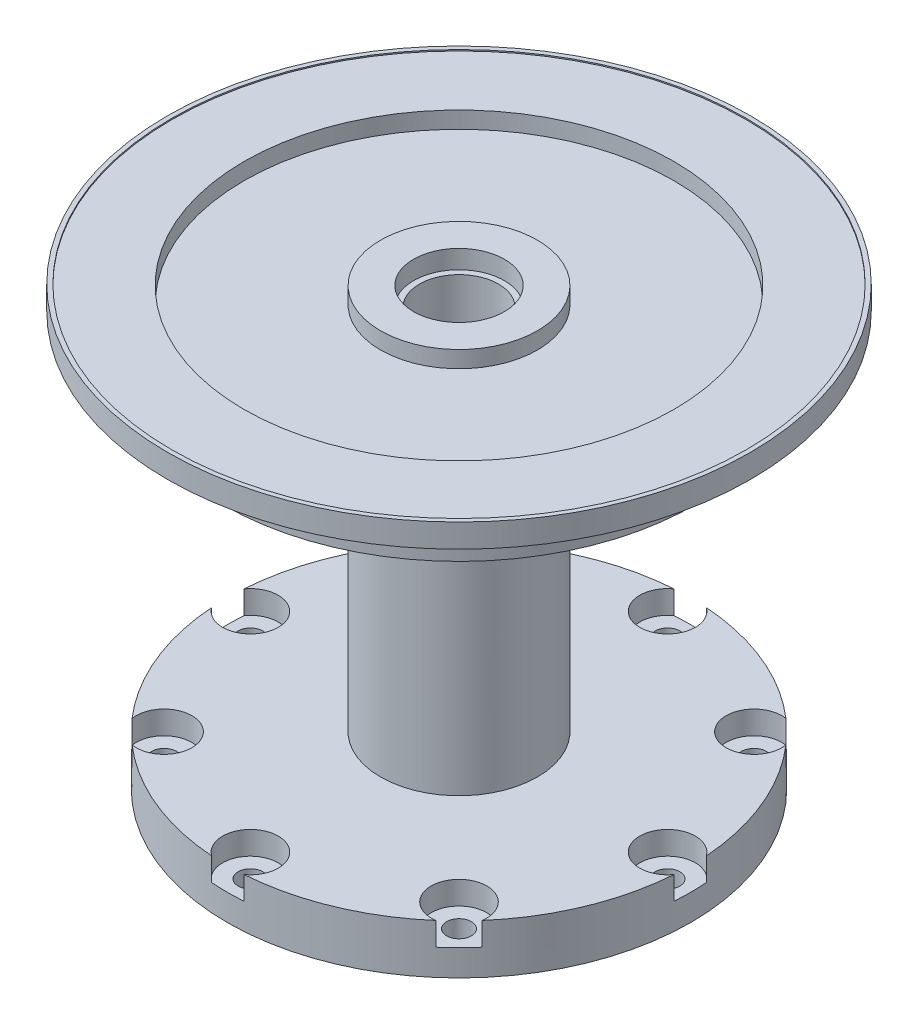
SolidWorks part; units mm, degrees
material "AISI 304"
ref_plane "Front Plane" through (0, 0, 0) normal (0, 0, 1) x (1, 0, 0)
ref_plane "Top Plane" through (0, 0, 0) normal (0, 1, 0) x (1, 0, 0)
ref_plane "Right Plane" through (0, 0, 0) normal (1, 0, 0) x (0, 0, -1)
sketch "Sketch1" plane through (0, 0, 0) normal (0, 1, 0) x (1, 0, 0)
  circle A0 centre (0, 0) radius 38.1
  dimension "D1" = 76.2
extrude "Boss-Extrude1" add sketch "Sketch1" along normal blind 4.826
sketch "Sketch2" plane through (0, 4.826, 0) normal (0, 1, 0) x (1, 0, 0)
  circle A0 centre (0, 0) radius 38.1 construction
  circle A1 centre (0, 0) radius 38.1
extrude "Boss-Extrude2" add sketch "Sketch2" along normal blind 3.302 draft 70 draft outward yes
sketch "Sketch3" plane through (0, 8.128, 0) normal (0, 1, 0) x (1, 0, 0)
  circle A0 centre (0, 0) radius 47.1722 construction
  circle A1 centre (0, 0) radius 47.1722
extrude "Boss-Extrude3" add sketch "Sketch3" along normal blind 3.81
sketch "Sketch4" plane through (0, 11.938, 0) normal (0, 1, 0) x (1, 0, 0)
  circle A3 centre (0, 0) radius 46.4722
  circle A4 centre (0, 0) radius 46.4722
  dimension "D1" = 0.7
extrude "Cut-Extrude1" cut sketch "Sketch4" against normal blind 0.2
sketch "Sketch6" plane through (0, 11.738, 0) normal (0, 1, 0) x (1, 0, 0)
  circle A1 centre (0, 0) radius 12.7
  circle A2 centre (0, 0) radius 34.7722
  circle A3 centre (0, 0) radius 34.7722
  dimension "D2" = 25.4
  dimension "D1" = 11.7
extrude "Cut-Extrude2" cut sketch "Sketch6" against normal blind 2.7
sketch "Sketch7" plane through (0, 11.738, 0) normal (0, 1, 0) x (1, 0, 0)
  circle A0 centre (0, 0) radius 5.35
  dimension "D1" = 10.7
sketch "Sketch8" plane through (0, 0, 0) normal (0, -1, 0) x (1, 0, 0)
  circle A1 centre (0, 0) radius 12.7
  circle A3 centre (0, 0) radius 12.7
  dimension "D1" = 0
extrude "Boss-Extrude4" add sketch "Sketch8" along normal blind 50.8
sketch "Sketch10" plane through (0, 11.738, 0) normal (0, 1, 0) x (1, 0, 0)
  circle A0 centre (0, 0) radius 7.35
  dimension "D1" = 14.7
extrude "Cut-Extrude5" cut sketch "Sketch10" against normal blind 3
sketch "Sketch11" plane through (0, 0, 0) normal (0, -1, 0) x (1, 0, 0)
  circle A0 centre (0, 0) radius 6.4
  dimension "D1" = 12.8
ref_plane "Plane2" through (0, -50.8, 0) normal (0, -1, 0) x (-1, 0, 0)
sketch "Sketch13" plane through (0, -50.8, 0) normal (0, -1, 0) x (-1, 0, 0)
  circle A0 centre (0, 0) radius 6.4 construction
  circle A1 centre (0, 0) radius 6.4
extrude "Cut-Extrude9" cut sketch "Sketch13" against normal through all
sketch "Sketch15" plane through (0, -50.8, 0) normal (0, -1, 0) x (1, 0, 0)
  circle A1 centre (0, 0) radius 37.5
  circle A2 centre (0, 0) radius 37.5
  dimension "D1" = 0
extrude "Boss-Extrude6" add sketch "Sketch15" along normal blind 8
sketch "Sketch16" plane through (0, -58.8, 0) normal (0, -1, 0) x (1, 0, 0)
  circle A0 centre (0, 0) radius 5.35 construction
  circle A1 centre (0, 33.75) radius 2
  circle A2 centre (0, 33.75) radius 2
  circle A3 centre (23.8649, 23.8649) radius 2
  circle A4 centre (23.8649, 23.8649) radius 2
  circle A5 centre (33.75, 0) radius 2
  circle A6 centre (33.75, 0) radius 2
  circle A7 centre (23.8649, -23.8649) radius 2
  circle A8 centre (23.8649, -23.8649) radius 2
  circle A9 centre (0, -33.75) radius 2
  circle A10 centre (0, -33.75) radius 2
  circle A11 centre (-23.8649, -23.8649) radius 2
  circle A12 centre (-23.8649, -23.8649) radius 2
  circle A13 centre (-33.75, 0) radius 2
  circle A14 centre (-33.75, 0) radius 2
  circle A15 centre (-23.8649, 23.8649) radius 2
  circle A16 centre (-23.8649, 23.8649) radius 2
  circle A17 centre (0, 0) radius 5.35
  dimension "D1" = 0
  dimension "D2" = 0
  dimension "D3" = 0
  dimension "D4" = 0
  dimension "D5" = 0
  dimension "D6" = 0
  dimension "D7" = 0
  dimension "D8" = 0
extrude "Cut-Extrude10" cut sketch "Sketch16" against normal up to next
sketch "Sketch17" plane through (0, -58.8, 0) normal (0, -1, 0) x (1, 0, 0)
  circle A0 centre (0, 0) radius 19.21 construction
  circle A1 centre (0, 0) radius 20.71 construction
  circle A2 centre (0, 0) radius 19.21
  circle A3 centre (0, 0) radius 20.71
extrude "Cut-Extrude11" cut sketch "Sketch17" against normal blind 3
sketch "Sketch19" plane through (0, -50.8, 0) normal (0, 1, 0) x (1, 0, 0)
  circle A1 centre (23.8649, 23.8649) radius 4.5
  circle A2 centre (0, 33.75) radius 4.5
  circle A3 centre (0, 33.75) radius 4.5
  circle A4 centre (33.75, 0) radius 4.5
  circle A5 centre (23.8649, -23.8649) radius 4.5
  circle A6 centre (0, -33.75) radius 4.5
  circle A7 centre (-23.8649, -23.8649) radius 4.5
  circle A8 centre (-33.75, 0) radius 4.5
  circle A9 centre (-23.8649, 23.8649) radius 4.5
  point P19 (0, 0)
  dimension "D1" = 2.5
  dimension "D2" = 8
extrude "Cut-Extrude12" cut sketch "Sketch19" against normal blind 3.75
